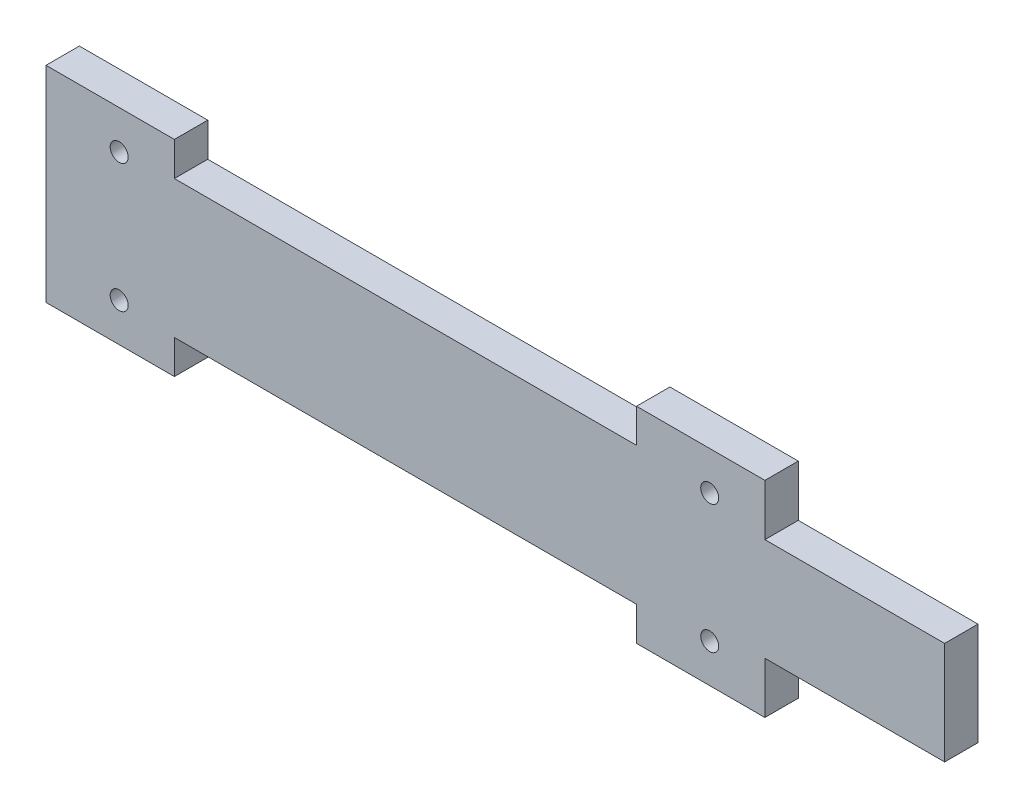
SolidWorks part; units mm, degrees
ref_plane "Alzado" through (0, 0, 0) normal (0, 0, 1) x (1, 0, 0)
ref_plane "Planta" through (0, 0, 0) normal (0, 1, 0) x (1, 0, 0)
ref_plane "Vista lateral" through (0, 0, 0) normal (1, 0, 0) x (0, 0, -1)
sketch "Sketch1" plane through (0, 0, 0) normal (0, 0, 1) x (1, 0, 0)
  line L0 (-103.144, -40) -> (-103.144, 40)
  line L1 (-103.144, 40) -> (-53.144, 40)
  line L2 (-53.144, 40) -> (-53.144, 26.8041)
  line L3 (-53.144, 26.8041) -> (126.856, 26.8041)
  line L4 (126.856, 26.8041) -> (126.856, 40)
  line L5 (126.856, 40) -> (176.856, 40)
  line L6 (176.856, 40) -> (176.856, 20)
  line L7 (176.856, 20) -> (246.856, 20)
  line L8 (246.856, 20) -> (246.856, -20)
  line L10 (176.856, -20) -> (246.856, -20)
  line L11 (176.856, -40) -> (176.856, -20)
  line L12 (126.856, -40) -> (176.856, -40)
  line L13 (126.856, -26.8041) -> (126.856, -40)
  line L14 (-53.144, -26.8041) -> (126.856, -26.8041)
  line L15 (-53.144, -40) -> (-53.144, -26.8041)
  line L16 (-103.144, -40) -> (-53.144, -40)
  circle A0 centre (-74.644, 25) radius 3.5
  circle A1 centre (155.356, 25) radius 3.5
  circle A2 centre (155.356, -25) radius 3.5
  circle A3 centre (-74.644, -25) radius 3.5
  dimension "D1" = 7
  dimension "D5" = 7
  dimension "D7" = 7
  dimension "D8" = 7
  dimension "D2" = 50
  dimension "D3" = 180
  dimension "D4" = 50
  dimension "D6" = 350
  dimension "D9" = 25
  dimension "D10" = 25
  dimension "D11" = 25
  dimension "D12" = 25
  dimension "D13" = 230
  dimension "D14" = 230
  dimension "D15" = 28.5
  dimension "D16" = 28.5
extrude "Boss-Extrude1" add sketch "Sketch1" along normal blind 13
